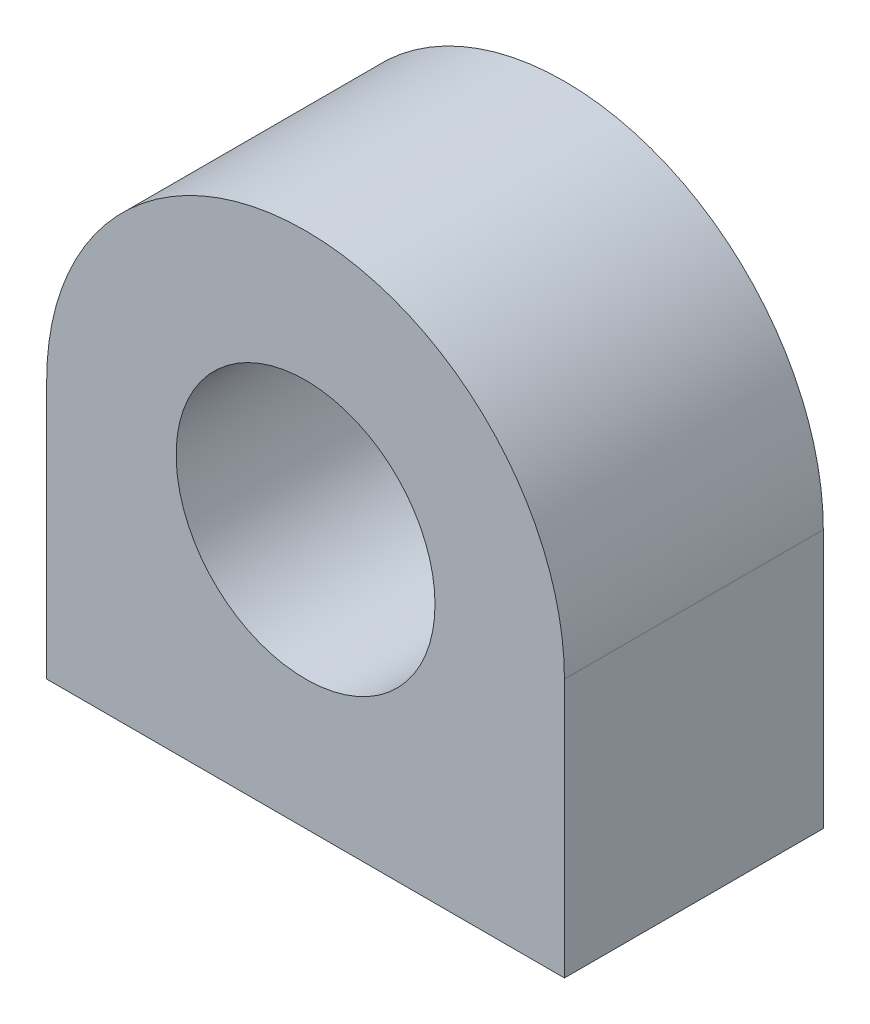
SolidWorks part; units mm, degrees
other "Markup1"
sketch "Sketch2" plane through (0, 20, 10) normal (-0.8773, 0.0469, 0.4777) x (0.4789, 0.0198, 0.8776)
ref_plane "Front Plane" through (0, 0, 0) normal (0, 0, 1) x (1, 0, 0)
ref_plane "Top Plane" through (0, 0, 0) normal (0, 1, 0) x (1, 0, 0)
ref_plane "Right Plane" through (0, 0, 0) normal (1, 0, 0) x (0, 0, -1)
sketch "Sketch1" plane through (0, 0, 0) normal (0, 0, 1) x (1, 0, 0)
  line L0 (0, 0) -> (20, 0)
  line L1 (20, 0) -> (20, 10)
  line L2 (0, 0) -> (0, 10)
  arc A0 (0, 10) -> (20, 10) centre (10, 10) cw
  circle A1 centre (10, 10) radius 5
  dimension "D2" = 10
  dimension "D3" = 10
  dimension "D1" = 20
extrude "Boss-Extrude1" add sketch "Sketch1" along normal blind 10
